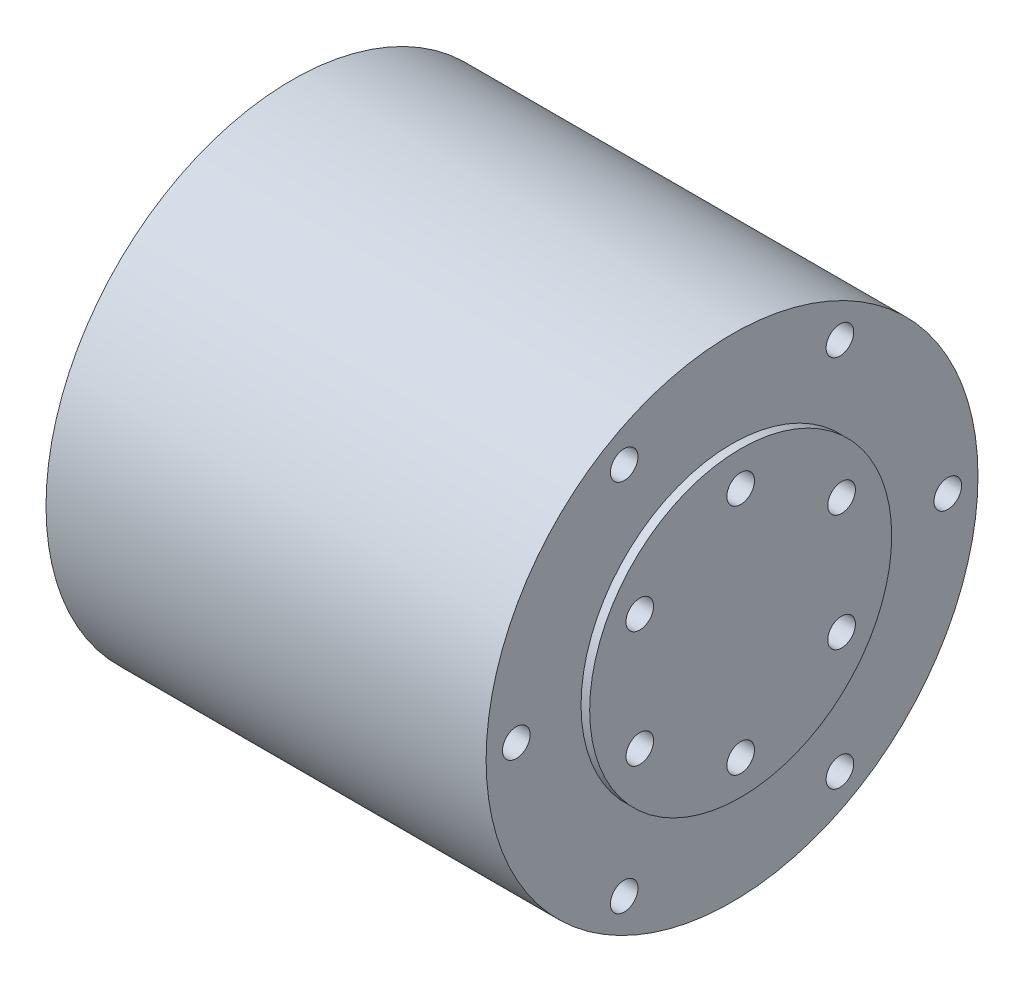
SolidWorks part; units mm, degrees
ref_plane "前视基准面" through (0, 0, 0) normal (0, 0, 1) x (1, 0, 0)
ref_plane "上视基准面" through (0, 0, 0) normal (0, 1, 0) x (1, 0, 0)
ref_plane "右视基准面" through (0, 0, 0) normal (1, 0, 0) x (0, 0, -1)
other "Configuration Table"
sketch "草图1" plane through (0, 0, 0) normal (1, 0, 0) x (0, 0, -1)
  circle A0 centre (0, 0) radius 28.5
  dimension "D1" = 57
extrude "凸台-拉伸1" add sketch "草图1" along normal blind 51
sketch "草图2" plane through (51, 0, 0) normal (1, 0, 0) x (0, 0, -1)
  circle A0 centre (0, 0) radius 17.5
  dimension "D1" = 35
extrude "凸台-拉伸2" add sketch "草图2" along normal blind 1
sketch "草图3" plane through (0, 0, 0) normal (-1, 0, 0) x (0, 0, 1)
  line L0 (-1000, 0) -> (49000, 0) construction
  line L1 (0, 0) -> (35355.3391, 35355.3391) construction
  circle A0 centre (0, 0) radius 19
  circle A1 centre (13.435, 13.435) radius 1.6
  circle A2 centre (13.435, -13.435) radius 1.6
  circle A3 centre (-13.435, -13.435) radius 1.6
  circle A4 centre (-13.435, 13.435) radius 1.6
  point P18 (0, 0)
  dimension "D1" = 38
  dimension "D3" = 3.2
  dimension "D2" = 45
  dimension "D4" = 4
extrude "切除-拉伸1" cut sketch "草图3" against normal blind 5 contours A4 | A3 | A2 | A1
sketch "草图4" plane through (51, 0, 0) normal (1, 0, 0) x (0, 0, -1)
  line L0 (0, -1000) -> (0, 49000) construction
  line L1 (0, 0) -> (25000, -43301.2702) construction
  circle A0 centre (0, 0) radius 25
  circle A1 centre (-12.5, 21.6506) radius 1.6
  circle A2 centre (12.5, 21.6506) radius 1.6
  circle A3 centre (25, 0) radius 1.6
  circle A4 centre (12.5, -21.6506) radius 1.6
  circle A5 centre (-12.5, -21.6506) radius 1.6
  circle A6 centre (-25, 0) radius 1.6
  point P22 (0, 0)
  dimension "D1" = 50
  dimension "D3" = 3.2
  dimension "D2" = 30
  dimension "D4" = 6
extrude "切除-拉伸2" cut sketch "草图4" against normal blind 5 contours A1 | A6 | A5 | A4 | A3 | A2
sketch "草图5" plane through (52, 0, 0) normal (1, 0, 0) x (0, 0, -1)
  circle A0 centre (0, 0) radius 13.5
  circle A1 centre (0, 13.5) radius 1.6
  circle A2 centre (11.6913, 6.75) radius 1.6
  circle A3 centre (11.6913, -6.75) radius 1.6
  circle A4 centre (0, -13.5) radius 1.6
  circle A5 centre (-11.6913, -6.75) radius 1.6
  circle A6 centre (-11.6913, 6.75) radius 1.6
  point P17 (0, 0)
  dimension "D1" = 27
  dimension "D2" = 3.2
  dimension "D3" = 6
extrude "切除-拉伸3" cut sketch "草图5" against normal blind 5 contours A6 | A5 | A4 | A3 | A2 | A1
